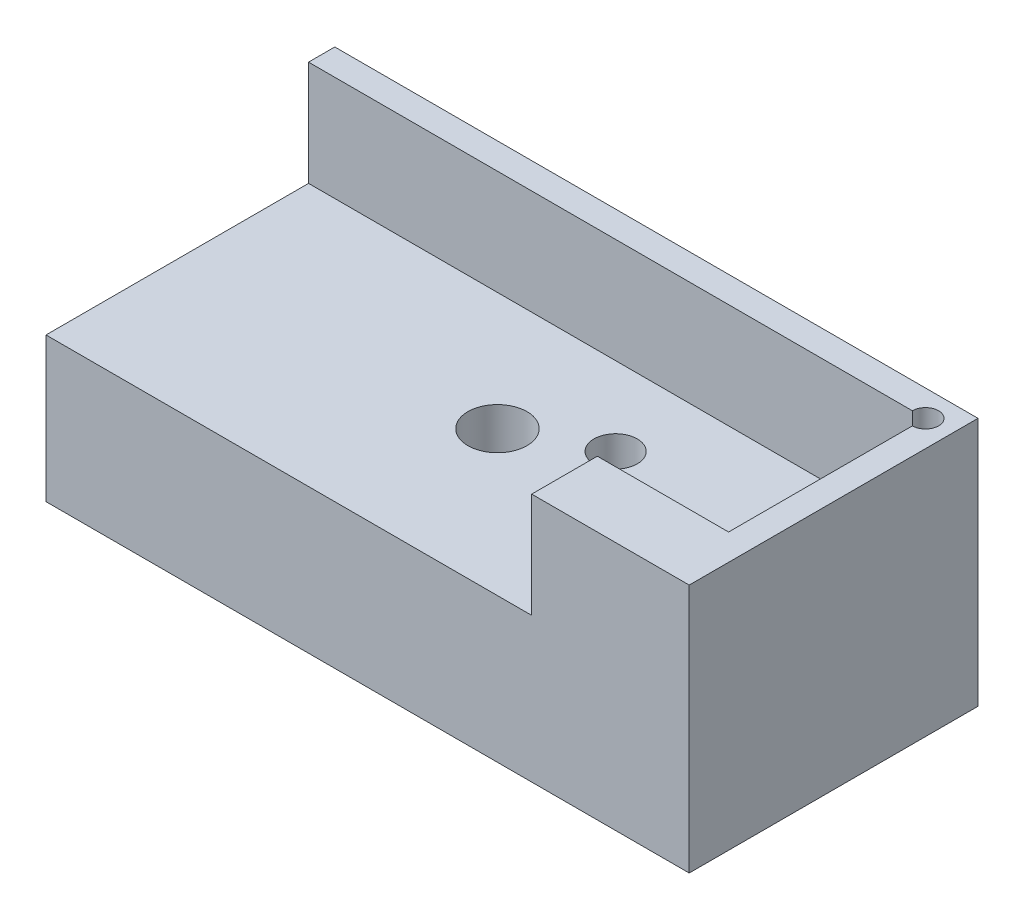
SolidWorks part; units mm, degrees
material "6061 合金"
ref_plane "前视基准面" through (0, 0, 0) normal (0, 0, 1) x (1, 0, 0)
ref_plane "上视基准面" through (0, 0, 0) normal (0, 1, 0) x (1, 0, 0)
ref_plane "右视基准面" through (0, 0, 0) normal (1, 0, 0) x (0, 0, -1)
sketch "草图1" plane through (0, 0, 0) normal (0, 1, 0) x (1, 0, 0)
  line L1 (-23.5, 9) -> (23.5, 9)
  line L2 (-23.5, 9) -> (-23.5, -9)
  line L3 (-23.5, -9) -> (23.5, -9)
  line L4 (23.5, 9) -> (23.5, -9)
  line L5 (-23.5, 9) -> (23.5, -9) construction
  line L6 (-23.5, -9) -> (23.5, 9) construction
  point P0 (0, 0)
  dimension "D1" = 47
  dimension "D2" = 18
extrude "凸台-拉伸1" add sketch "草图1" along normal blind 6
sketch "草图2" plane through (0, 6, 0) normal (0, 1, 0) x (1, 0, 0)
  line L1 (23.5, 9) -> (-23.5, 9) construction
  line L3 (23.5, 9) -> (-23.5, 9)
  line L12 (-23.5, -9) -> (23.5, -9) construction
  line L13 (-23.5, -9) -> (23.5, -9)
  line L19 (23.5, -9) -> (23.5, 9) construction
  line L20 (23.5, -9) -> (23.5, 9)
  line L21 (-23.5, -11) -> (25.5, -11)
  line L22 (25.5, -11) -> (25.5, 11)
  line L23 (25.5, 11) -> (-23.5, 11)
  line L24 (-23.5, -11) -> (-23.5, -9)
  line L25 (-23.5, 9) -> (-23.5, 11)
  dimension "D1" = 2
extrude "凸台-拉伸2" add sketch "草图2" along normal blind 8 and the other way through all
sketch "草图15" plane through (0, 0, 10) normal (0, 1, 0) x (1, 0, 0)
  line L4 (-23.5, -1) -> (25.5, -1)
  line L5 (-23.5, 21) -> (-23.5, -1)
  line L6 (25.5, 21) -> (-23.5, 21)
  line L7 (25.5, -1) -> (25.5, 21)
  line L12 (-23.5, -1) -> (25.5, -1)
  line L13 (-23.5, 21) -> (-23.5, -1)
  line L14 (25.5, 21) -> (-23.5, 21)
  line L15 (25.5, -1) -> (25.5, 21)
  dimension "D1" = 0
extrude "凸台-拉伸3" add sketch "草图15" against normal blind 5
sketch "草图12" plane through (-23.5, 0, 0) normal (-1, 0, 0) x (0, 0, 1)
  line L5 (9, 6) -> (11, 6)
  line L6 (9, 6) -> (9, 14)
  line L7 (9, 14) -> (11, 14)
  line L8 (11, 6) -> (11, 14)
extrude "切除-拉伸5" cut sketch "草图12" against normal offset from surface (37 mm away) 10 up to face at (23.5, 10, 0)
sketch "草图19" plane through (0, 0, 9) normal (0, 0, -1) x (-1, 0, 0)
  line L4 (-23.5, 6) -> (-13.5, 6)
  line L5 (-13.5, 6) -> (-13.5, 14)
  line L6 (-13.5, 14) -> (-23.5, 14)
  line L7 (-23.5, 14) -> (-23.5, 6)
  line L8 (-23.5, 6) -> (-13.5, 6)
  line L10 (-13.5, 14) -> (-23.5, 14)
  line L11 (-23.5, 14) -> (-23.5, 6)
  line L15 (-13.5, 6) -> (-13.5, 14)
  dimension "D1" = 0
extrude "凸台-拉伸4" add sketch "草图19" along normal blind 3
sketch "草图13" plane through (0, 14, 0) normal (0, 1, 0) x (1, 0, 0)
  circle A0 centre (23.5, 9) radius 1
  point P3 (0, 0)
extrude "切除-拉伸6" cut sketch "草图13" against normal up to surface (8 mm away) up to face at (4.5, 6, 2.6667)
sketch "草图5" plane through (0, -5, 0) normal (0, -1, 0) x (1, 0, 0)
  line L1 (-6.622, 9.4855) -> (18.378, 9.4855)
  line L2 (-6.622, 9.4855) -> (-6.622, -15.5145)
  line L3 (-6.622, -15.5145) -> (18.378, -15.5145)
  line L4 (18.378, 9.4855) -> (18.378, -15.5145)
  line L5 (-6.622, 9.4855) -> (18.378, -15.5145) construction
  line L6 (-6.622, -15.5145) -> (18.378, 9.4855) construction
  circle A0 centre (5.878, -3.0145) radius 2.3876 construction
  circle A1 centre (5.878, -3.0145) radius 2.3876 construction
  dimension "D1" = 25
  dimension "D2" = 25
extrude "切除-拉伸1" cut sketch "草图5" along normal up to surface (2.844 mm away)
sketch "草图3" plane through (0, -5, 0) normal (0, 1, 0) x (1, 0, 0)
  line L0 (-0.122, 9) -> (-0.122, 0.0145) construction
  line L1 (23.5, -6) -> (23.5, 8) construction
  line L3 (22.5, 9) -> (-23.5, 9) construction
  line L5 (-0.122, 0.0145) -> (23.5, 0.0145) construction
  circle A0 centre (-0.122, 0.0145) radius 1.3881
  circle A1 centre (-0.122, 0.0145) radius 2.5 construction
hole_wizard "打孔尺寸(%根据)内六角圆柱头螺钉的类型2" positions "3D草图1" profile "草图4" counterbore size "M4" standard "GB" end condition through all
sketch3d "3D草图1"
  point P0 (-0.122, -5, -0.0145)
sketch "草图4" plane through (-0.122, -5, -0.0145) normal (1, 0, 0) x (0, 0, -1)
  line L0 (0, 0) -> (0, 19)
  line L1 (0, 19) -> (2.25, 19)
  line L3 (2.25, 19) -> (2.25, 4.6)
  line L4 (2.25, 4.6) -> (4, 4.6)
  line L5 (4, 4.6) -> (4, 0)
  line L7 (4, 0) -> (0, 0)
  line L11 (0, -6.35) -> (0, 107.95) construction
  dimension "通孔孔直径" = 4.5
  dimension "通孔孔深度" = 19
  dimension "柱形沉头孔直径" = 8
  dimension "柱形沉头孔深度" = 4.6
sketch "草图6" plane through (0, -2.156, 0) normal (0, -1, 0) x (1, 0, 0)
  circle A2 centre (5.878, -3.0145) radius 5
  circle A4 centre (5.878, -3.0145) radius 2.3876 construction
  point P2 (0, 0)
hole_wizard "M4 螺纹孔4" positions "3D草图2" profile "草图20" tap size "M4" standard "GB" end condition through all
sketch3d "3D草图2"
  point P0 (5.878, -2.156, -3.0145)
sketch "草图20" plane through (5.878, -2.156, -3.0145) normal (1, 0, 0) x (0, 0, -1)
  line L0 (0, 0) -> (0, 16.156)
  line L1 (0, 16.156) -> (1.65, 16.156)
  line L2 (1.65, 16.156) -> (1.65, 0)
  line L5 (1.65, 0) -> (0, 0)
  line L11 (0, -6.35) -> (0, 107.95) construction
  dimension "通孔螺纹孔钻头直径" = 3.3
  dimension "通孔螺纹孔钻头深度" = 16.156
cosmetic thread "孔螺蚊线6" parameters "D2"=4
sketch "草图17" plane through (18.378, 0, 0) normal (-1, 0, 0) x (0, 0, 1)
  line L4 (-11, -5) -> (9.4855, -5)
  line L5 (9.4855, -5) -> (9.4855, -2.156)
  line L6 (9.4855, -2.156) -> (-11, -2.156)
  line L7 (-11, -2.156) -> (-11, -5)
  line L10 (9.4855, -2.156) -> (-11, -2.156)
  line L14 (-11, -2.156) -> (-11, -5)
  line L15 (-11, -5) -> (9.4855, -5)
  line L16 (9.4855, -5) -> (9.4855, -2.156)
  dimension "D1" = 0
extrude "切除-拉伸8" cut sketch "草图17" against normal blind 0.5
sketch "草图18" plane through (0, -5, 0) normal (0, -1, 0) x (-1, 0, 0)
  line L0 (6.622, -9.4855) -> (6.622, 11) construction
  line L1 (-18.878, -9.4855) -> (6.622, -9.4855) construction
  circle A0 centre (6.622, -9.4855) radius 1
  point P3 (0, 0)
  point P6 (0, 0)
extrude "切除-拉伸9" cut sketch "草图18" against normal up to surface (2.844 mm away)
fillet "圆角1" radius 1 1 edges at (18.878, -3.578, 9.4855)
